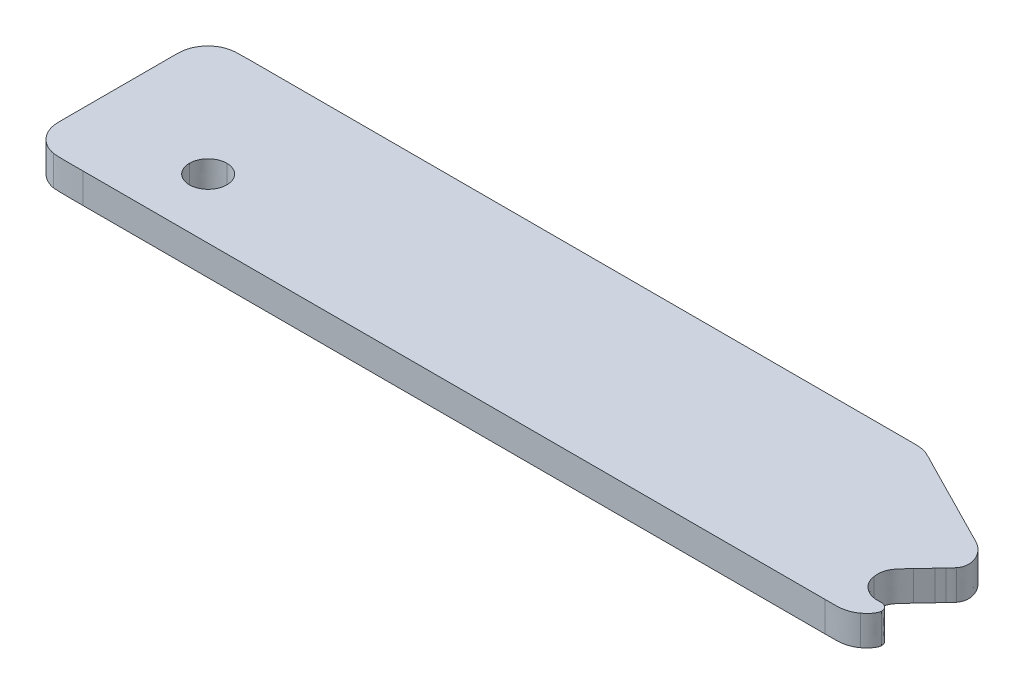
SolidWorks part; units mm, degrees
ref_plane "Front Plane" through (0, 0, 0) normal (0, 0, 1) x (1, 0, 0)
ref_plane "Top Plane" through (0, 0, 0) normal (0, 1, 0) x (1, 0, 0)
ref_plane "Right Plane" through (0, 0, 0) normal (1, 0, 0) x (0, 0, -1)
sketch "Sketch1" plane through (0, 0, 0) normal (0, 1, 0) x (1, 0, 0)
  spline S0 degree 3 poles (174.8406, 5.6295) (175.3918, 5.6272) (175.9155, 5.7307) (176.4598, 5.4343) knots 0 0 0 0 1 1 1 1
  spline S1 degree 3 poles (176.4598, 5.4343) (177.0317, 5.1242) (177.2659, 4.7453) (177.2866, 4.0906) knots 0 0 0 0 1 1 1 1
  spline S2 degree 3 poles (177.2866, 4.0906) (177.3141, 3.1261) (176.0809, 1.9478) (175.4538, 1.4862) knots 0 0 0 0 1 1 1 1
  spline S3 degree 3 poles (175.4538, 1.4862) (173.4075, -0.0297) (171.3542, 0.239) (169.1218, 0.239) knots 0 0 0 0 1 1 1 1
  spline S4 degree 3 poles (169.1218, 0.239) (164.7602, 0.239) (160.3988, 0.239) (156.0442, 0.239) knots 0 0 0 0 1 1 1 1
  spline S5 degree 3 poles (156.0442, 0.239) (147.3212, 0.239) (138.5982, 0.239) (129.8821, 0.239) knots 0 0 0 0 1 1 1 1
  spline S6 degree 3 poles (129.8821, 0.239) (112.3879, 0.239) (94.8937, 0.239) (77.3926, 0.239) knots 0 0 0 0 1 1 1 1
  spline S7 degree 3 poles (77.3926, 0.239) (59.8847, 0.239) (42.3836, 0.239) (24.8756, 0.239) knots 0 0 0 0 1 1 1 1
  spline S8 degree 3 poles (24.8756, 0.239) (20.5279, 0.239) (16.1802, 0.239) (11.8393, 0.239) knots 0 0 0 0 1 1 1 1
  spline S9 degree 3 poles (11.8393, 0.239) (11.0194, 0.239) (6.2101, 0.199) (5.3833, 0.3496) knots 0 0 0 0 1 1 1 1
  spline S10 degree 3 poles (5.3833, 0.3496) (3.0681, 0.7975) (1.194, 2.4786) (0.505, 4.7248) knots 0 0 0 0 1 1 1 1
  spline S11 degree 3 poles (0.505, 4.7248) (0.1812, 5.7859) (0.2225, 6.8332) (0.2225, 7.9081) knots 0 0 0 0 1 1 1 1
  spline S12 degree 3 poles (0.2225, 7.9081) (0.2225, 8.9898) (0.2225, 10.0785) (0.2225, 11.1603) knots 0 0 0 0 1 1 1 1
  spline S13 degree 3 poles (0.2225, 11.1603) (0.2225, 13.3375) (0.2225, 15.5079) (0.2225, 17.6784) knots 0 0 0 0 1 1 1 1
  spline S14 degree 3 poles (0.2225, 17.6784) (0.2225, 22.0261) (0.2225, 26.3738) (0.2225, 30.7215) knots 0 0 0 0 1 1 1 1
  spline S15 degree 3 poles (0.2225, 30.7215) (0.2225, 31.7964) (0.1949, 32.8437) (0.5326, 33.9047) knots 0 0 0 0 1 1 1 1
  spline S16 degree 3 poles (0.5326, 33.9047) (0.9115, 35.0692) (1.511, 35.958) (2.4411, 36.7642) knots 0 0 0 0 1 1 1 1
  spline S17 degree 3 poles (2.4411, 36.7642) (4.398, 38.4454) (6.4237, 38.2939) (8.6905, 38.2939) knots 0 0 0 0 1 1 1 1
  spline S18 degree 3 poles (8.6905, 38.2939) (13.0451, 38.2939) (17.3997, 38.2939) (21.7543, 38.2939) knots 0 0 0 0 1 1 1 1
  spline S19 degree 3 poles (21.7543, 38.2939) (30.4635, 38.2939) (39.1659, 38.2939) (47.8751, 38.2939) knots 0 0 0 0 1 1 1 1
  spline S20 degree 3 poles (47.8751, 38.2939) (65.3624, 38.2939) (82.8497, 38.2939) (100.337, 38.2939) knots 0 0 0 0 1 1 1 1
  spline S21 degree 3 poles (100.337, 38.2939) (109.0875, 38.2939) (117.8312, 38.2939) (126.5817, 38.2939) knots 0 0 0 0 1 1 1 1
  spline S22 degree 3 poles (126.5817, 38.2939) (130.957, 38.2939) (135.3322, 38.2939) (139.7075, 38.2939) knots 0 0 0 0 1 1 1 1
  spline S23 degree 3 poles (139.7075, 38.2939) (141.8917, 38.2939) (144.0828, 38.2939) (146.267, 38.2939) knots 0 0 0 0 1 1 1 1
  spline S24 degree 3 poles (146.267, 38.2939) (147.3625, 38.2939) (148.4581, 38.2939) (149.5536, 38.2939) knots 0 0 0 0 1 1 1 1
  spline S25 degree 3 poles (149.5536, 38.2939) (150.656, 38.2939) (151.7171, 38.2788) (152.7851, 37.8733) knots 0 0 0 0 1 1 1 1
  spline S26 degree 3 poles (152.7851, 37.8733) (153.8118, 37.4808) (154.7419, 36.9225) (155.7065, 36.4264) knots 0 0 0 0 1 1 1 1
  spline S27 degree 3 poles (155.7065, 36.4264) (156.6781, 35.9304) (157.6427, 35.4412) (158.6142, 34.945) knots 0 0 0 0 1 1 1 1
  spline S28 degree 3 poles (158.6142, 34.945) (160.5504, 33.9597) (162.4865, 32.9744) (164.4226, 31.9891) knots 0 0 0 0 1 1 1 1
  spline S29 degree 3 poles (164.4226, 31.9891) (166.3588, 30.9969) (168.2949, 30.0116) (170.2311, 29.0263) knots 0 0 0 0 1 1 1 1
  spline S30 degree 3 poles (170.2311, 29.0263) (171.1957, 28.5303) (172.1672, 28.0411) (173.1318, 27.545) knots 0 0 0 0 1 1 1 1
  spline S31 degree 3 poles (173.1318, 27.545) (174.1034, 27.0555) (175.0887, 26.6354) (175.9224, 25.8845) knots 0 0 0 0 1 1 1 1
  spline S32 degree 3 poles (175.9224, 25.8845) (177.4176, 24.5408) (178.7405, 21.9364) (177.2866, 20.0209) knots 0 0 0 0 1 1 1 1
  spline S33 degree 3 poles (177.2866, 20.0209) (176.9559, 19.5869) (176.5632, 19.2147) (176.1911, 18.822) knots 0 0 0 0 1 1 1 1
  spline S34 degree 3 poles (176.1911, 18.822) (175.819, 18.4225) (175.4538, 18.0227) (175.0818, 17.63) knots 0 0 0 0 1 1 1 1
  spline S35 degree 3 poles (175.0818, 17.63) (174.3445, 16.8376) (173.6004, 16.0383) (172.8562, 15.246) knots 0 0 0 0 1 1 1 1
  spline S36 degree 3 poles (172.8562, 15.246) (171.3266, 13.5992) (169.7212, 12.3727) (170.1346, 9.658) knots 0 0 0 0 1 1 1 1
  spline S37 degree 3 poles (170.1346, 9.658) (170.3275, 8.4178) (170.8236, 7.5496) (171.7814, 6.7435) knots 0 0 0 0 1 1 1 1
  spline S38 degree 3 poles (171.7814, 6.7435) (172.2361, 6.3645) (172.7184, 6.0889) (173.2765, 5.896) knots 0 0 0 0 1 1 1 1
  spline S39 degree 3 poles (173.2765, 5.896) (173.5384, 5.8065) (173.8002, 5.7375) (174.0689, 5.6895) knots 0 0 0 0 1 1 1 1
  spline S40 degree 3 poles (174.0689, 5.6895) (174.1998, 5.6695) (174.3307, 5.6545) (174.4617, 5.6395) knots 0 0 0 0 1 1 1 1
  spline S41 degree 3 poles (174.4617, 5.6395) (174.5238, 5.6395) (174.5925, 5.6345) (174.6545, 5.6345) knots 0 0 0 0 1 1 1 1
  spline S42 degree 3 poles (174.6545, 5.6345) (174.6891, 5.6295) (174.7166, 5.6295) (174.7511, 5.6295) knots 0 0 0 0 1 1 1 1
  spline S43 degree 3 poles (174.7511, 5.6295) (174.7856, 5.6295) (174.9095, 5.6345) (174.8406, 5.6295) knots 0 0 0 0 1 1 1 1
  spline S44 degree 3 poles (29.5954, 12.9378) (29.5954, 10.7467) (27.8177, 8.969) (25.6266, 8.969) knots 0 0 0 0 1 1 1 1
  spline S45 degree 3 poles (25.6266, 8.969) (23.4355, 8.969) (21.6579, 10.7467) (21.6579, 12.9378) knots 0 0 0 0 1 1 1 1
  spline S46 degree 3 poles (21.6579, 12.9378) (21.6579, 15.1288) (23.4355, 16.9065) (25.6266, 16.9065) knots 0 0 0 0 1 1 1 1
  spline S47 degree 3 poles (25.6266, 16.9065) (27.8177, 16.9065) (29.5954, 15.1288) (29.5954, 12.9378) knots 0 0 0 0 1 1 1 1
extrude "Boss-Extrude1" add sketch "Sketch1" along normal blind 6.35 contours S19 S20 S21 S22 S23 S24 S25 S26 S27 S28 S29 S30 S31 S32 S33 S34 S35 S36 S37 S38 S39 S40 S41 S42 S43 S0 S1 S2 S3 S4 S5 S6 S7 S8 S9 S10 S11 S12 S13 S14 S15 S16 S17 S18
